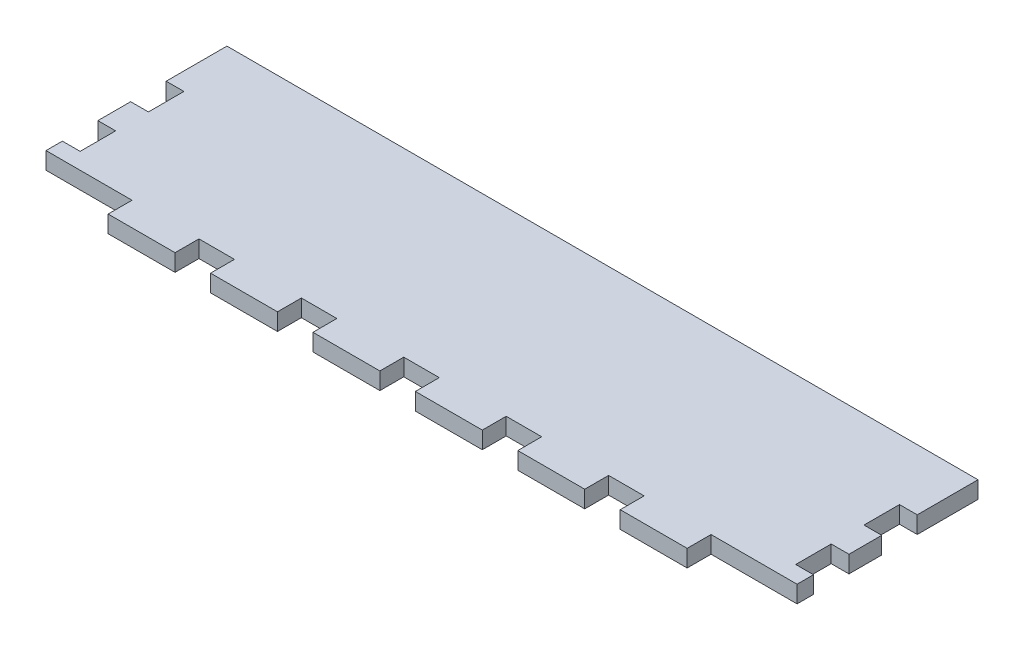
SolidWorks part; units mm, degrees
ref_plane "Front Plane" through (0, 0, 0) normal (0, 0, 1) x (1, 0, 0)
ref_plane "Top Plane" through (0, 0, 0) normal (0, 1, 0) x (1, 0, 0)
ref_plane "Right Plane" through (0, 0, 0) normal (1, 0, 0) x (0, 0, -1)
sketch "Sketch1" plane through (0, 0, 0) normal (0, 1, 0) x (1, 0, 0)
  line L2 (-139.7, -28.575) -> (-139.7, 28.575)
  line L3 (-139.7, 28.575) -> (139.7, 28.575)
  line L4 (139.7, -28.575) -> (139.7, 28.575)
  line L5 (-139.7, -28.575) -> (139.7, 28.575) construction
  line L6 (-139.7, 28.575) -> (139.7, -28.575) construction
  line L11 (-139.7, -28.575) -> (139.7, -28.575)
  point P0 (0, 0)
  dimension "D1" = 57.15
  dimension "D2" = 279.4
extrude "Boss-Extrude1" add sketch "Sketch1" along normal blind 6.35
sketch "Sketch3" plane through (0, 0, 0) normal (0, 1, 0) x (1, 0, 0)
  line L0 (-139.7, -28.575) -> (139.7, -28.575) construction
  line L1 (-107.696, -28.575) -> (-107.696, -37.465)
  line L2 (-107.696, -37.465) -> (-82.804, -37.465)
  line L3 (-82.804, -37.465) -> (-82.804, -28.575)
  line L4 (-82.804, -28.575) -> (-107.696, -28.575)
  line L5 (-69.596, -28.575) -> (-69.596, -37.465)
  line L6 (-69.596, -37.465) -> (-44.704, -37.465)
  line L7 (-44.704, -37.465) -> (-44.704, -28.575)
  line L8 (-44.704, -28.575) -> (-69.596, -28.575)
  line L9 (-31.496, -28.575) -> (-31.496, -37.465)
  line L10 (-31.496, -37.465) -> (-6.604, -37.465)
  line L11 (-6.604, -37.465) -> (-6.604, -28.575)
  line L12 (-6.604, -28.575) -> (-31.496, -28.575)
  line L13 (6.604, -28.575) -> (6.604, -37.465)
  line L14 (6.604, -37.465) -> (31.496, -37.465)
  line L15 (31.496, -37.465) -> (31.496, -28.575)
  line L16 (31.496, -28.575) -> (6.604, -28.575)
  line L17 (44.704, -28.575) -> (44.704, -37.465)
  line L18 (44.704, -37.465) -> (69.596, -37.465)
  line L19 (69.596, -37.465) -> (69.596, -28.575)
  line L20 (69.596, -28.575) -> (44.704, -28.575)
  line L21 (82.804, -28.575) -> (82.804, -37.465)
  line L22 (82.804, -37.465) -> (107.696, -37.465)
  line L23 (107.696, -37.465) -> (107.696, -28.575)
  line L24 (107.696, -28.575) -> (82.804, -28.575)
  point P0 (-95.25, -28.575)
  point P6 (-57.15, -28.575)
  point P14 (-19.05, -28.575)
  point P19 (19.05, -28.575)
  point P24 (57.15, -28.575)
  point P29 (95.25, -28.575)
  dimension "D1" = 24.892
  dimension "D2" = 8.89
  dimension "D3" = 44.45
extrude "Boss-Extrude2" add sketch "Sketch3" along normal blind 6.35
sketch "Sketch4" plane through (0, 0, 0) normal (0, 1, 0) x (1, 0, 0)
  line L0 (-139.7, 28.575) -> (-139.7, -28.575) construction
  line L1 (139.7, 28.575) -> (-139.7, 28.575) construction
  line L2 (-146.304, 16.129) -> (-133.096, 16.129)
  line L3 (-146.304, 16.129) -> (-146.304, 2.921)
  line L4 (-146.304, 2.921) -> (-133.096, 2.921)
  line L5 (-133.096, 16.129) -> (-133.096, 2.921)
  line L6 (-146.304, 16.129) -> (-133.096, 2.921) construction
  line L7 (-146.304, 2.921) -> (-133.096, 16.129) construction
  line L8 (0, 0) -> (0, 63.6475) construction
  line L9 (-146.304, -9.271) -> (-133.096, -9.271)
  line L10 (-133.096, -9.271) -> (-133.096, -22.479)
  line L11 (-146.304, -22.479) -> (-133.096, -22.479)
  line L12 (-146.304, -9.271) -> (-146.304, -22.479)
  line L13 (146.304, 2.921) -> (133.096, 16.129) construction
  line L14 (146.304, 16.129) -> (133.096, 2.921) construction
  line L15 (146.304, -9.271) -> (146.304, -22.479)
  line L16 (146.304, -22.479) -> (133.096, -22.479)
  line L17 (133.096, -9.271) -> (133.096, -22.479)
  line L18 (146.304, -9.271) -> (133.096, -9.271)
  line L19 (133.096, 16.129) -> (133.096, 2.921)
  line L20 (146.304, 2.921) -> (133.096, 2.921)
  line L21 (146.304, 16.129) -> (146.304, 2.921)
  line L22 (146.304, 16.129) -> (133.096, 16.129)
  point P0 (-139.7, 9.525)
  point P1 (-139.7, 9.525)
  point P25 (139.7, 9.525)
  dimension "D1" = 13.208
  dimension "D2" = 13.208
  dimension "D3" = 19.05
  dimension "D5" = 2
extrude "Cut-Extrude2" cut sketch "Sketch4" along normal through all
sketch "Sketch5" plane through (0, 6.35, 0) normal (0, 1, 0) x (1, 0, 0)
  line L0 (-107.696, -37.465) -> (-82.804, -37.465) construction
  line L1 (-139.7, 28.575) -> (171.8176, 28.575)
  line L2 (-139.7, 28.575) -> (-139.7, 26.035)
  line L3 (-139.7, 26.035) -> (171.8176, 26.035)
  line L4 (171.8176, 28.575) -> (171.8176, 26.035)
  dimension "D1" = 63.5
extrude "Cut-Extrude3" cut sketch "Sketch5" against normal through all
sketch "Sketch6" plane through (0, 6.35, 0) normal (0, 1, 0) x (1, 0, 0)
  line L0 (139.7, 16.129) -> (139.7, 26.035) construction
  line L1 (-139.7, 26.035) -> (139.7, 26.035)
  line L2 (-139.7, 26.035) -> (-139.7, 38.735)
  line L3 (-139.7, 38.735) -> (139.7, 38.735)
  line L4 (139.7, 26.035) -> (139.7, 38.735)
  line L5 (-107.696, -37.465) -> (-82.804, -37.465) construction
  dimension "D1" = 76.2
extrude "Boss-Extrude3" add sketch "Sketch6" against normal up to surface (6.35 mm away) up to face at (0, 0, 19.2809)
